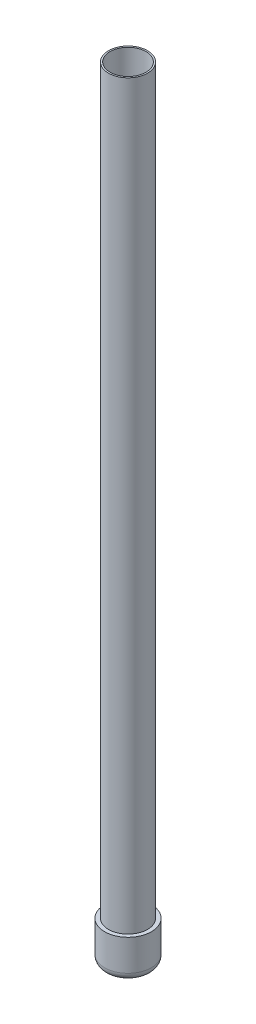
SolidWorks part; units mm, degrees
ref_plane "Front Plane" through (0, 0, 0) normal (0, 0, 1) x (1, 0, 0)
ref_plane "Top Plane" through (0, 0, 0) normal (0, 1, 0) x (1, 0, 0)
ref_plane "Right Plane" through (0, 0, 0) normal (1, 0, 0) x (0, 0, -1)
sketch "Sketch1" plane through (0, 0, 0) normal (0, 1, 0) x (1, 0, 0)
  circle A0 centre (0, 0) radius 12.5
  dimension "D1" = 25
extrude "Boss-Extrude1" add sketch "Sketch1" along normal blind 500
sketch "Sketch3" plane through (0, 0, 0) normal (0, -1, 0) x (1, 0, 0)
  circle A0 centre (0, 0) radius 15
  point P2 (0, 0)
  dimension "D1" = 30
  dimension "D2" = 0
extrude "Boss-Extrude2" add sketch "Sketch3" against normal blind 25
fillet "Fillet2" radius 5 1 edges at (0, 0, -15)
shell "Shell1" thickness 1
